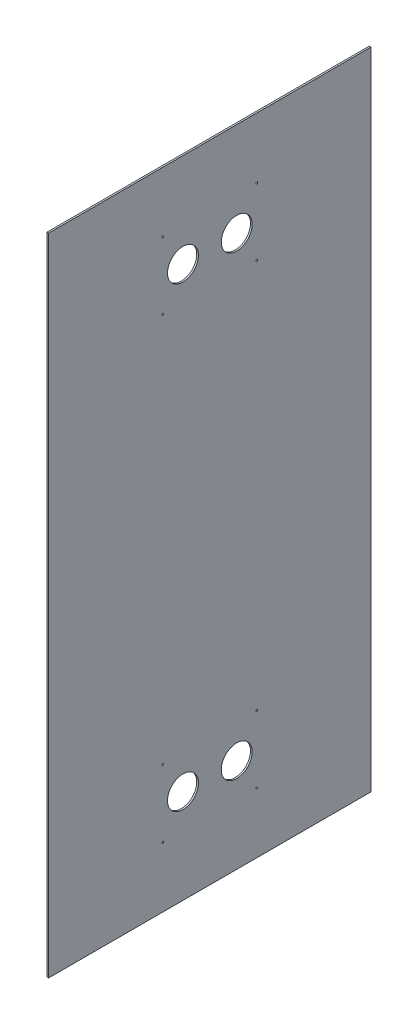
SolidWorks part; units mm, degrees
ref_plane "Front Plane" through (0, 0, 0) normal (0, 0, 1) x (1, 0, 0)
ref_plane "Top Plane" through (0, 0, 0) normal (0, 1, 0) x (1, 0, 0)
ref_plane "Right Plane" through (0, 0, 0) normal (1, 0, 0) x (0, 0, -1)
sketch "Sketch1" plane through (0, 0, 0) normal (1, 0, 0) x (0, 0, -1)
  line L1 (304.8, -609.6) -> (-304.8, -609.6)
  line L2 (304.8, -609.6) -> (304.8, 609.6)
  line L3 (304.8, 609.6) -> (-304.8, 609.6)
  line L4 (-304.8, -609.6) -> (-304.8, 609.6)
  line L5 (304.8, -609.6) -> (-304.8, 609.6) construction
  line L6 (304.8, 609.6) -> (-304.8, -609.6) construction
  point P0 (0, 0)
  dimension "D1" = 609.6
  dimension "D2" = 1219.2
extrude "Boss-Extrude1" add sketch "Sketch1" along normal blind 3.175
sketch "Sketch2" plane through (3.175, 0, 0) normal (1, 0, 0) x (0, 0, -1)
  line L0 (-304.8, -609.6) -> (304.8, -609.6) construction
  line L1 (-50.8, -431.8) -> (50.8, -431.8) construction
  line L3 (-304.8, 609.6) -> (-304.8, -609.6) construction
  circle A0 centre (-50.8, -431.8) radius 29.21
  circle A1 centre (50.8, -431.8) radius 29.21
  dimension "D4" = 58.42
  dimension "D1" = 177.8
  dimension "D2" = 101.6
  dimension "D3" = 254
extrude "Cut-Extrude1" cut sketch "Sketch2" against normal through all
sketch "Sketch3" plane through (3.175, 0, 0) normal (1, 0, 0) x (0, 0, -1)
  line L0 (-88.9, -495.3) -> (88.9, -495.3) construction
  line L1 (-88.9, -368.3) -> (-88.9, -495.3) construction
  line L2 (88.9, -368.3) -> (88.9, -495.3) construction
  circle A0 centre (-88.9, -368.3) radius 1.5875
  circle A1 centre (88.9, -368.3) radius 1.5875
  circle A2 centre (-50.8, -431.8) radius 29.21 construction
  circle A3 centre (50.8, -431.8) radius 29.21 construction
  circle A4 centre (-88.9, -495.3) radius 1.5875
  circle A5 centre (88.9, -495.3) radius 1.5875
  dimension "D2" = 38.1
  dimension "D3" = 3.175
  dimension "D4" = 38.1
  dimension "D6" = 127
  dimension "D1" = 63.5
  dimension "D5" = 63.5
extrude "Cut-Extrude2" cut sketch "Sketch3" against normal through all
mirror "Mirror1" about plane through (0, 0, 0) normal (0, 1, 0) of "Cut-Extrude2", "Cut-Extrude1"
